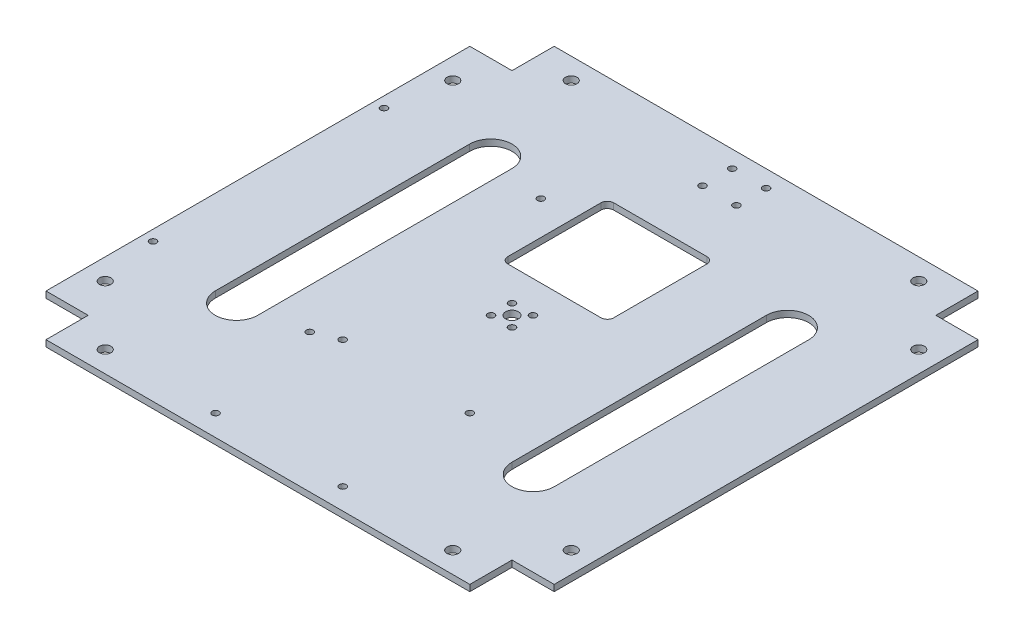
SolidWorks part; units mm, degrees
ref_plane "前视基准面" through (0, 0, 0) normal (0, 0, 1) x (1, 0, 0)
ref_plane "上视基准面" through (0, 0, 0) normal (0, 1, 0) x (1, 0, 0)
ref_plane "右视基准面" through (0, 0, 0) normal (1, 0, 0) x (0, 0, -1)
sketch "草图1" plane through (0, 0, 0) normal (0, 1, 0) x (1, 0, 0)
  line L1 (-119.9, -119.9) -> (119.9, -119.9)
  line L2 (-119.9, -119.9) -> (-119.9, 119.9)
  line L3 (-119.9, 119.9) -> (119.9, 119.9)
  line L4 (119.9, -119.9) -> (119.9, 119.9)
  line L5 (-119.9, -119.9) -> (119.9, 119.9) construction
  line L6 (-119.9, 119.9) -> (119.9, -119.9) construction
  circle A0 centre (0, 0) radius 3
  circle A1 centre (0, 0) radius 7 construction
  circle A2 centre (4.9497, 4.9497) radius 1.6
  circle A3 centre (4.9497, -4.9497) radius 1.6
  circle A4 centre (-4.9497, -4.9497) radius 1.6
  circle A5 centre (-4.9497, 4.9497) radius 1.6
  point P0 (0, 0)
  point P14 (0, 0)
  point P17 (0, 0)
  point P20 (0, 0)
  point P23 (0, 0)
  dimension "D3" = 14
  dimension "D4" = 6
  dimension "D5" = 3.2
  dimension "D1" = 239.8
  dimension "D2" = 239.8
  dimension "D6" = 4
extrude "凸台-拉伸1" add sketch "草图1" along normal blind 3
sketch "草图2" plane through (0, 3, 0) normal (0, 1, 0) x (1, 0, 0)
  line L0 (-119.9, 0) -> (119.9, 0) construction
  line L1 (-119.9, 119.9) -> (-119.9, -119.9) construction
  line L2 (119.9, -119.9) -> (119.9, 119.9) construction
  line L3 (0, 119.9) -> (0, -119.9) construction
  line L4 (119.9, 119.9) -> (-119.9, 119.9) construction
  line L5 (-119.9, -119.9) -> (119.9, -119.9) construction
  line L6 (119.9, 119.9) -> (100, 119.9)
  line L7 (-119.9, 119.9) -> (-100, 119.9)
  line L8 (-119.9, 119.9) -> (-119.9, 100)
  line L9 (-119.9, 100) -> (-100, 100)
  line L10 (-100, 119.9) -> (-100, 100)
  line L11 (119.9, 119.9) -> (119.9, 100)
  line L12 (119.9, 100) -> (100, 100)
  line L13 (100, 119.9) -> (100, 100)
  line L14 (119.9, -119.9) -> (119.9, -100)
  line L15 (119.9, -119.9) -> (100, -119.9)
  line L16 (100, -119.9) -> (100, -100)
  line L17 (119.9, -100) -> (100, -100)
  line L18 (-119.9, -119.9) -> (-100, -119.9)
  line L19 (-119.9, -119.9) -> (-119.9, -100)
  line L20 (-119.9, -100) -> (-100, -100)
  line L21 (-100, -119.9) -> (-100, -100)
  line L22 (-8, 104.9) -> (8, 104.9) construction
  line L23 (-8, 111.9) -> (8, 111.9) construction
  line L24 (-8, 111.9) -> (-8, 97.9) construction
  line L25 (-8, 97.9) -> (8, 97.9) construction
  line L26 (8, 111.9) -> (8, 97.9) construction
  line L27 (-8, 111.9) -> (8, 97.9) construction
  line L28 (-8, 97.9) -> (8, 111.9) construction
  circle A0 centre (-8, 111.9) radius 1.6
  circle A1 centre (8, 111.9) radius 1.6
  circle A2 centre (8, 97.9) radius 1.6
  circle A3 centre (-8, 97.9) radius 1.6
  point P17 (0, 104.9)
  point P33 (0, 0)
  dimension "D7" = 3.2
  dimension "D1" = 19.9
  dimension "D2" = 19.9
  dimension "D4" = 16
  dimension "D5" = 14
  dimension "D6" = 8
  dimension "D3" = 4
extrude "切除-拉伸2" cut sketch "草图2" against normal blind 3 contours L18 L21 L20 L19 | L14 L17 L16 L15 | L6 L13 L12 L11 | L8 L7 L10 L9 | A1 | A0 | A3 | A2
sketch "草图3" plane through (0, 3, 0) normal (0, 1, 0) x (1, 0, 0)
  line L0 (0, 119.9) -> (0, -119.9) construction
  line L1 (100, 119.9) -> (-100, 119.9) construction
  line L2 (-100, -119.9) -> (100, -119.9) construction
  line L3 (-30, -79.9) -> (30, -79.9) construction
  line L4 (-30, -49.9) -> (30, -49.9) construction
  line L5 (-30, -49.9) -> (-30, -109.9) construction
  line L6 (-30, -109.9) -> (30, -109.9) construction
  line L7 (30, -49.9) -> (30, -109.9) construction
  line L8 (-30, -49.9) -> (30, -109.9) construction
  line L9 (-30, -109.9) -> (30, -49.9) construction
  circle A0 centre (-30, -49.9) radius 1.6
  circle A1 centre (30, -49.9) radius 1.6
  circle A2 centre (-30, -109.9) radius 1.6
  circle A3 centre (30, -109.9) radius 1.6
  point P6 (0, -79.9)
  dimension "D4" = 3.2
  dimension "D1" = 60
  dimension "D2" = 60
  dimension "D3" = 10
extrude "切除-拉伸3" cut sketch "草图3" against normal blind 3
sketch "草图4" plane through (0, 3, 0) normal (0, 1, 0) x (1, 0, 0)
  line L0 (-70, 60) -> (-70, -60) construction
  line L1 (-60, 60) -> (-60, -60)
  line L2 (-80, 60) -> (-80, -60)
  line L3 (70, 60) -> (70, -60) construction
  line L4 (80, 60) -> (80, -60)
  line L5 (60, 60) -> (60, -60)
  line L6 (0, 119.9) -> (0, -119.9) construction
  line L7 (100, 119.9) -> (-100, 119.9) construction
  line L8 (-100, -119.9) -> (100, -119.9) construction
  line L9 (-119.9, 0) -> (119.9, 0) construction
  line L10 (-119.9, 100) -> (-119.9, -100) construction
  line L11 (119.9, -100) -> (119.9, 100) construction
  line L13 (-25, 70) -> (25, 70)
  line L14 (-25, 70) -> (-25, 20)
  line L15 (-25, 20) -> (25, 20)
  line L16 (25, 70) -> (25, 20)
  line L17 (-25, 70) -> (25, 20) construction
  line L18 (-25, 20) -> (25, 70) construction
  arc A0 (-60, 60) -> (-80, 60) centre (-70, 60) ccw
  arc A1 (-80, -60) -> (-60, -60) centre (-70, -60) ccw
  arc A2 (80, 60) -> (60, 60) centre (70, 60) ccw
  arc A3 (60, -60) -> (80, -60) centre (70, -60) ccw
  point P2 (-70, 0)
  point P7 (70, 0)
  point P20 (0, 45)
  dimension "D1" = 20
  dimension "D2" = 20
  dimension "D3" = 60
  dimension "D4" = 120
  dimension "D5" = 50
  dimension "D6" = 50
  dimension "D7" = 20
extrude "切除-拉伸4" cut sketch "草图4" against normal blind 3
fillet "圆角1" radius 3 4 edges at (25, 1.5, -20) (25, 1.5, -70) (-25, 1.5, -20) (-25, 1.5, -70)
sketch "草图5" plane through (0, 3, 0) normal (0, 1, 0) x (1, 0, 0)
  line L0 (100, -100) -> (-100, 100) construction
  line L1 (-119.9, 100) -> (-109.95, 100) construction
  line L2 (-119.9, 100) -> (-119.9, 82) construction
  line L3 (-119.9, 82) -> (-109.95, 82) construction
  line L4 (-109.95, 100) -> (-109.95, 82) construction
  line L5 (0, 119.9) -> (0, -119.9) construction
  line L6 (100, 119.9) -> (-100, 119.9) construction
  line L7 (-100, -119.9) -> (100, -119.9) construction
  line L8 (-119.9, 0) -> (119.9, 0) construction
  line L9 (-119.9, 100) -> (-119.9, -100) construction
  line L10 (119.9, -100) -> (119.9, 100) construction
  circle A0 centre (-109.95, 82) radius 2.7
  circle A1 centre (-82, 109.95) radius 2.7
  circle A2 centre (-109.95, -82) radius 2.7
  circle A3 centre (-82, -109.95) radius 2.7
  circle A4 centre (109.95, 82) radius 2.7
  circle A5 centre (82, 109.95) radius 2.7
  circle A6 centre (109.95, -82) radius 2.7
  circle A7 centre (82, -109.95) radius 2.7
  dimension "D3" = 5.4
  dimension "D1" = 9.95
  dimension "D2" = 18
extrude "切除-拉伸5" cut sketch "草图5" against normal blind 3
sketch "草图6" plane through (0, 3, 0) normal (0, 1, 0) x (1, 0, 0)
  line L0 (0, 0) -> (-119.9, 0) construction
  line L1 (-119.9, 100) -> (-119.9, -100) construction
  line L2 (-77.9, 54.5) -> (-77.9, -54.5) construction
  line L3 (-114.9, -54.5) -> (-40.9, -54.5) construction
  line L4 (-114.9, -54.5) -> (-114.9, 54.5) construction
  line L5 (-114.9, 54.5) -> (-40.9, 54.5) construction
  line L6 (-40.9, -54.5) -> (-40.9, 54.5) construction
  line L7 (-114.9, -54.5) -> (-40.9, 54.5) construction
  line L8 (-114.9, 54.5) -> (-40.9, -54.5) construction
  circle A0 centre (-114.9, 54.5) radius 1.6
  circle A1 centre (-40.9, 54.5) radius 1.6
  circle A2 centre (-114.9, -54.5) radius 1.6
  circle A3 centre (-40.9, -54.5) radius 1.6
  point P5 (-77.9, 0)
  dimension "D4" = 3.2
  dimension "D1" = 74
  dimension "D2" = 109
  dimension "D3" = 5
extrude "切除-拉伸7" cut sketch "草图6" against normal blind 3 contours A1 | A3 | L4 L3 L6 L5 | A0 | A2
